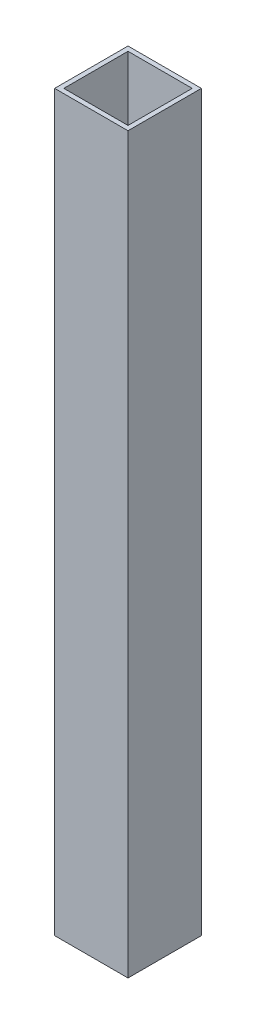
SolidWorks part; units mm, degrees
ref_plane "Front Plane" through (0, 0, 0) normal (0, 0, 1) x (1, 0, 0)
ref_plane "Top Plane" through (0, 0, 0) normal (0, 1, 0) x (1, 0, 0)
ref_plane "Right Plane" through (0, 0, 0) normal (1, 0, 0) x (0, 0, -1)
other "Configuration Table"
sketch "Sketch1" plane through (0, 0, 0) normal (0, 1, 0) x (1, 0, 0)
  line L1 (12.7, 12.7) -> (-12.7, 12.7)
  line L2 (12.7, 12.7) -> (12.7, -12.7)
  line L3 (12.7, -12.7) -> (-12.7, -12.7)
  line L4 (-12.7, 12.7) -> (-12.7, -12.7)
  line L5 (12.7, 12.7) -> (-12.7, -12.7) construction
  line L6 (12.7, -12.7) -> (-12.7, 12.7) construction
  line L7 (11.1125, -11.1125) -> (-11.1125, -11.1125)
  line L8 (11.1125, -11.1125) -> (11.1125, 11.1125)
  line L9 (11.1125, 11.1125) -> (-11.1125, 11.1125)
  line L10 (-11.1125, -11.1125) -> (-11.1125, 11.1125)
  line L11 (11.1125, -11.1125) -> (-11.1125, 11.1125) construction
  line L12 (11.1125, 11.1125) -> (-11.1125, -11.1125) construction
  point P0 (0, 0)
  point P6 (0, 0)
  dimension "D1" = 25.4
  dimension "D2" = 1.5875
extrude "Boss-Extrude1" add sketch "Sketch1" along normal blind 254
